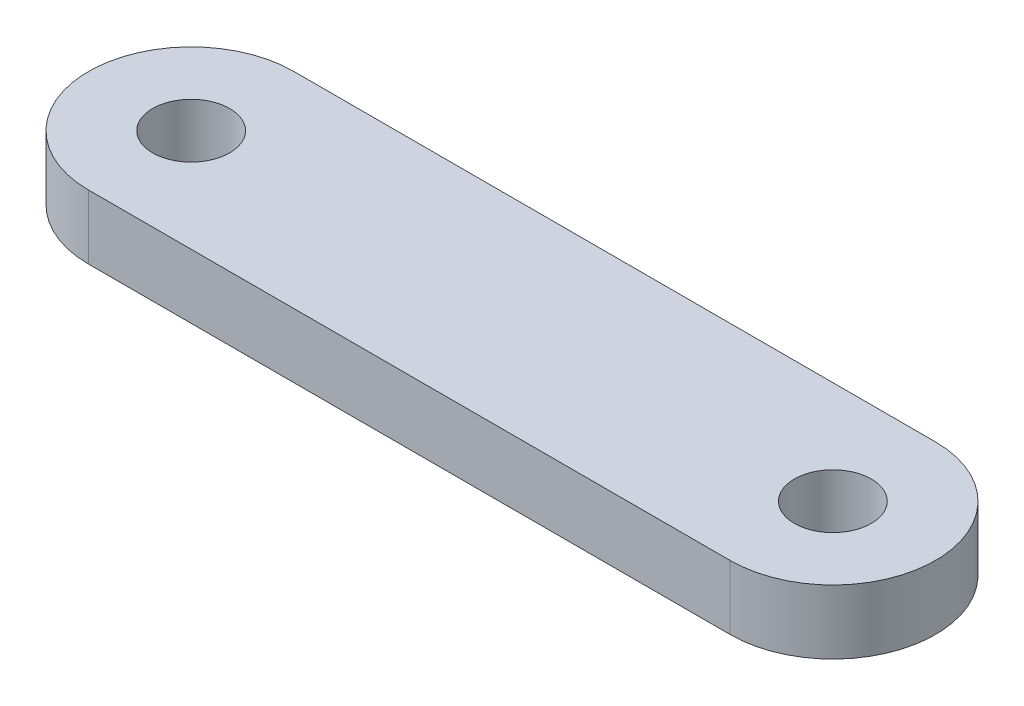
SolidWorks part; units mm, degrees
ref_plane "前基準面" through (0, 0, 0) normal (0, 0, 1) x (1, 0, 0)
ref_plane "上基準面" through (0, 0, 0) normal (0, 1, 0) x (1, 0, 0)
ref_plane "右基準面" through (0, 0, 0) normal (1, 0, 0) x (0, 0, -1)
sketch "草圖1" plane through (0, 0, 0) normal (0, 1, 0) x (1, 0, 0)
  line L0 (-35.9568, 0) -> (39.8148, 0) construction
  line L1 (-25, 0) -> (25, 0) construction
  line L2 (-25, 8) -> (25, 8)
  line L3 (-25, -8) -> (25, -8)
  arc A0 (-25, 8) -> (-25, -8) centre (-25, 0) ccw
  arc A1 (25, -8) -> (25, 8) centre (25, 0) ccw
  circle A2 centre (-25, 0) radius 3
  circle A3 centre (25, 0) radius 3
  point P5 (0, 0)
  dimension "D2" = 8
  dimension "D3" = 6
  dimension "D1" = 50
extrude "填料-伸長1" add sketch "草圖1" along normal blind 5
